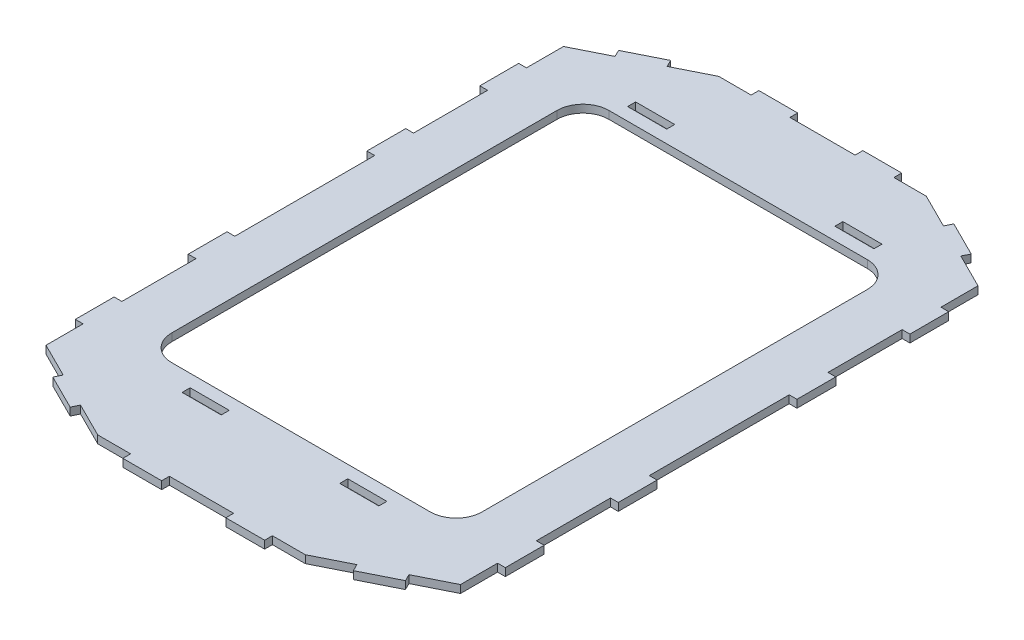
SolidWorks part; units mm, degrees
ref_plane "Front Plane" through (0, 0, 0) normal (0, 0, 1) x (1, 0, 0)
ref_plane "Top Plane" through (0, 0, 0) normal (0, 1, 0) x (1, 0, 0)
ref_plane "Right Plane" through (0, 0, 0) normal (1, 0, 0) x (0, 0, -1)
sketch "Sketch1" plane through (0, 0, 0) normal (0, 1, 0) x (1, 0, 0)
  line L0 (22.4968, -120.1354) -> (35.7886, -113.4895)
  line L1 (-57.7032, -120.1354) -> (-45.0032, -120.1354)
  line L2 (-97.7032, -100.1354) -> (-97.7032, -85.8129)
  line L3 (-57.7032, 119.8646) -> (-45.2032, 119.8646)
  line L4 (62.4968, -100.1354) -> (62.4968, -85.8129)
  line L5 (22.4968, 119.8646) -> (35.7886, 113.2187)
  line L6 (-97.7032, -100.1354) -> (-84.4114, -106.7813)
  line L7 (-97.7032, 99.8646) -> (-84.4114, 106.5105)
  line L11 (-17.6032, 119.8646) -> (-17.6032, -120.1354) construction
  line L12 (-97.7032, 2.4117) -> (-97.7032, 26.8971)
  line L16 (62.4968, 2.4117) -> (62.4968, 26.8971)
  line L17 (-17.6032, 93.7005) -> (-97.7032, 93.7005) construction
  line L18 (19.3759, -120.1354) -> (19.3759, -95.1354) construction
  line L19 (-65.2032, 92.1505) -> (-50.1032, 92.1505)
  line L20 (-65.2032, 92.1505) -> (-65.2032, 95.2505)
  line L21 (-65.2032, 95.2505) -> (-50.1032, 95.2505)
  line L22 (-50.1032, 92.1505) -> (-50.1032, 95.2505)
  line L23 (-65.2032, 92.1505) -> (-50.1032, 95.2505) construction
  line L24 (-65.2032, 95.2505) -> (-50.1032, 92.1505) construction
  line L25 (19.3759, -95.1354) -> (0.3759, -95.1354) construction
  line L26 (0.3759, -95.1354) -> (0.3759, -120.1354) construction
  line L27 (62.4968, -88.0623) -> (-97.7032, -88.0623) construction
  line L28 (-77.7032, 109.8646) -> (-82.9175, 120.2932) construction
  line L29 (-55.6105, -89.6123) -> (-40.5105, -89.6123)
  line L30 (-55.6105, -89.6123) -> (-55.6105, -86.5123)
  line L31 (-55.6105, -86.5123) -> (-40.5105, -86.5123)
  line L32 (-40.5105, -89.6123) -> (-40.5105, -86.5123)
  line L33 (-55.6105, -89.6123) -> (-40.5105, -86.5123) construction
  line L34 (-55.6105, -86.5123) -> (-40.5105, -89.6123) construction
  line L35 (-85.7531, 109.1938) -> (-72.3367, 115.902)
  line L36 (-85.7531, 109.1938) -> (-84.4114, 106.5105)
  line L37 (-72.3367, 115.902) -> (-70.995, 113.2187)
  line L38 (-77.7032, -110.1354) -> (-82.7032, -120.1354) construction
  line L39 (-85.7531, -109.4646) -> (-72.3367, -116.1728)
  line L40 (-85.7531, -109.4646) -> (-84.4114, -106.7813)
  line L41 (-72.3367, -116.1728) -> (-70.995, -113.4895)
  line L42 (-97.7032, 56.2196) -> (-97.7032, 70.5421) construction
  line L43 (-97.7032, 56.2196) -> (-97.7032, 41.8971) construction
  line L44 (-100.7032, 85.5421) -> (-97.7032, 85.5421)
  line L45 (-100.7032, 85.5421) -> (-100.7032, 70.5421)
  line L46 (-100.7032, 70.5421) -> (-97.7032, 70.5421)
  line L47 (-100.7032, 85.5421) -> (-97.7032, 78.0421) construction
  line L48 (-100.7032, 70.5421) -> (-97.7032, 78.0421) construction
  line L49 (-100.7032, 26.8971) -> (-97.7032, 26.8971)
  line L50 (-100.7032, 26.8971) -> (-100.7032, 41.8971)
  line L51 (-100.7032, 41.8971) -> (-97.7032, 41.8971)
  line L52 (-100.7032, 26.8971) -> (-97.7032, 34.3971) construction
  line L53 (-100.7032, 41.8971) -> (-97.7032, 34.3971) construction
  line L54 (-97.7032, 85.5421) -> (-97.7032, 99.8646)
  line L55 (-97.7032, 85.5421) -> (-97.7032, 99.8646) construction
  line L56 (-97.7032, 41.8971) -> (-97.7032, 70.5421)
  line L57 (-97.7032, 26.8971) -> (-97.7032, 2.4117) construction
  line L58 (-70.995, 113.2187) -> (-57.7032, 119.8646)
  line L59 (-70.995, -113.4895) -> (-57.7032, -120.1354)
  line L60 (-57.7032, 119.8646) -> (-45.2032, 119.8646) construction
  line L61 (-57.7032, -120.1354) -> (-45.0032, -120.1354) construction
  line L62 (-45.2032, 119.8646) -> (-45.2032, 122.8646)
  line L63 (-45.2032, 122.8646) -> (-30.2032, 122.8646)
  line L64 (-30.2032, 119.8646) -> (-30.2032, 122.8646)
  line L65 (-37.7032, 119.8646) -> (-30.2032, 122.8646) construction
  line L66 (-45.2032, 122.8646) -> (-37.7032, 119.8646) construction
  line L67 (-30.0032, -120.1354) -> (-17.6032, -120.1354) construction
  line L68 (-45.0032, -123.1354) -> (-30.0032, -123.1354)
  line L69 (-45.0032, -123.1354) -> (-45.0032, -120.1354)
  line L70 (-30.0032, -123.1354) -> (-30.0032, -120.1354)
  line L71 (-30.2032, 119.8646) -> (-5.0032, 119.8646)
  line L72 (-30.2032, 119.8646) -> (-17.6032, 119.8646) construction
  line L73 (-30.0032, -120.1354) -> (-5.2032, -120.1354)
  line L74 (14.8968, 92.1505) -> (14.8968, 95.2505)
  line L75 (29.9968, 92.1505) -> (29.9968, 95.2505)
  line L76 (29.9968, 92.1505) -> (14.8968, 92.1505)
  line L77 (29.9968, 95.2505) -> (14.8968, 95.2505)
  line L78 (-5.0032, 119.8646) -> (-5.0032, 122.8646)
  line L79 (9.9968, 122.8646) -> (-5.0032, 122.8646)
  line L80 (9.9968, 119.8646) -> (9.9968, 122.8646)
  line L81 (37.1302, 115.902) -> (35.7886, 113.2187)
  line L82 (50.5466, 109.1938) -> (37.1302, 115.902)
  line L83 (50.5466, 109.1938) -> (49.205, 106.5105)
  line L84 (65.4968, 85.5421) -> (62.4968, 85.5421)
  line L85 (65.4968, 85.5421) -> (65.4968, 70.5421)
  line L86 (65.4968, 70.5421) -> (62.4968, 70.5421)
  line L87 (65.4968, 41.8971) -> (62.4968, 41.8971)
  line L88 (65.4968, 26.8971) -> (65.4968, 41.8971)
  line L89 (65.4968, 26.8971) -> (62.4968, 26.8971)
  line L90 (50.5466, -109.4646) -> (49.205, -106.7813)
  line L91 (50.5466, -109.4646) -> (37.1302, -116.1728)
  line L92 (37.1302, -116.1728) -> (35.7886, -113.4895)
  line L93 (9.7968, -123.1354) -> (9.7968, -120.1354)
  line L94 (-5.2032, -123.1354) -> (-5.2032, -120.1354)
  line L95 (9.7968, -123.1354) -> (-5.2032, -123.1354)
  line L96 (20.404, -86.5123) -> (5.304, -89.6123) construction
  line L97 (20.404, -89.6123) -> (5.304, -86.5123) construction
  line L98 (5.304, -89.6123) -> (5.304, -86.5123)
  line L99 (20.404, -86.5123) -> (5.304, -86.5123)
  line L100 (20.404, -89.6123) -> (20.404, -86.5123)
  line L101 (20.404, -89.6123) -> (5.304, -89.6123)
  line L102 (9.7968, -120.1354) -> (22.4968, -120.1354)
  line L103 (49.205, -106.7813) -> (62.4968, -100.1354)
  line L104 (62.4968, 41.8971) -> (62.4968, 70.5421)
  line L105 (62.4968, 85.5421) -> (62.4968, 99.8646)
  line L106 (49.205, 106.5105) -> (62.4968, 99.8646)
  line L107 (9.9968, 119.8646) -> (22.4968, 119.8646)
  line L108 (-97.7032, 2.4117) -> (-97.7032, -27.1679)
  line L109 (62.4968, -70.8129) -> (62.4968, -42.1679)
  line L110 (-97.7032, -0.1354) -> (62.4968, -0.1354) construction
  line L111 (-100.7032, -85.8129) -> (-97.7032, -85.8129)
  line L112 (-100.7032, -85.8129) -> (-100.7032, -70.8129)
  line L113 (-100.7032, -70.8129) -> (-97.7032, -70.8129)
  line L114 (-100.7032, -42.1679) -> (-97.7032, -42.1679)
  line L115 (-100.7032, -27.1679) -> (-100.7032, -42.1679)
  line L116 (-100.7032, -27.1679) -> (-97.7032, -27.1679)
  line L117 (-97.7032, -42.1679) -> (-97.7032, -70.8129)
  line L118 (65.4968, -85.8129) -> (65.4968, -70.8129)
  line L119 (65.4968, -85.8129) -> (62.4968, -85.8129)
  line L120 (65.4968, -70.8129) -> (62.4968, -70.8129)
  line L121 (65.4968, -42.1679) -> (62.4968, -42.1679)
  line L122 (65.4968, -27.1679) -> (62.4968, -27.1679)
  line L123 (65.4968, -27.1679) -> (65.4968, -42.1679)
  line L124 (62.4968, -27.1679) -> (62.4968, 2.4117)
  line L130 (-67.5511, 87.2387) -> (32.3447, 87.2387)
  line L131 (-77.5511, 77.2387) -> (-77.5511, -71.6639)
  line L132 (-67.5511, -81.6639) -> (32.3447, -81.6639)
  line L133 (42.3447, 77.2387) -> (42.3447, -71.6639)
  line L134 (-77.5511, 87.2387) -> (42.3447, -81.6639) construction
  line L135 (-77.5511, -81.6639) -> (42.3447, 87.2387) construction
  arc A12 (-77.5511, -71.6639) -> (-67.5511, -81.6639) centre (-67.5511, -71.6639) ccw
  arc A13 (32.3447, -81.6639) -> (42.3447, -71.6639) centre (32.3447, -71.6639) ccw
  arc A14 (32.3447, 87.2387) -> (42.3447, 77.2387) centre (32.3447, 77.2387) cw
  arc A15 (-67.5511, 87.2387) -> (-77.5511, 77.2387) centre (-67.5511, 77.2387) ccw
  point P0 (-97.7032, -120.1354)
  point P1 (62.4968, 119.8646)
  point P2 (-97.7032, 119.8646)
  point P3 (62.4968, -120.1354)
  point P17 (-17.6032, -0.1354)
  point P24 (-57.6532, 93.7005)
  point P31 (-17.6032, 2.7874)
  point P37 (-17.6032, 58.2929)
  point P51 (-48.0605, -88.0623)
  point P61 (-79.0449, 112.5479)
  point P65 (-97.7032, 78.0421)
  point P68 (-79.0449, -112.8187)
  point P76 (-97.7032, 34.3971)
  point P80 (-37.7032, 119.8646)
  point P87 (-37.6032, -120.1354)
  point P126 (12.854, -88.0623)
  dimension "D9" = 10
  dimension "D1" = 40
  dimension "D2" = 20
  dimension "D3" = 40
  dimension "D4" = 20
  dimension "D5" = 40
  dimension "D6" = 20
  dimension "D7" = 20
  dimension "D8" = 40
  dimension "D10" = 15.1
  dimension "D11" = 3.1
  dimension "D24" = 25
  dimension "D25" = 19
  dimension "D26" = 3.1
  dimension "D27" = 15.1
  dimension "D28" = 15
  dimension "D29" = 3
  dimension "D30" = 15
  dimension "D31" = 3
  dimension "D32" = 15
  dimension "D33" = 15
  dimension "D34" = 3
  dimension "D35" = 3
  dimension "D36" = 15
  dimension "D37" = 3
  dimension "D38" = 15
  dimension "D39" = 3
extrude "Boss-Extrude1" add sketch "Sketch1" along normal blind 3
